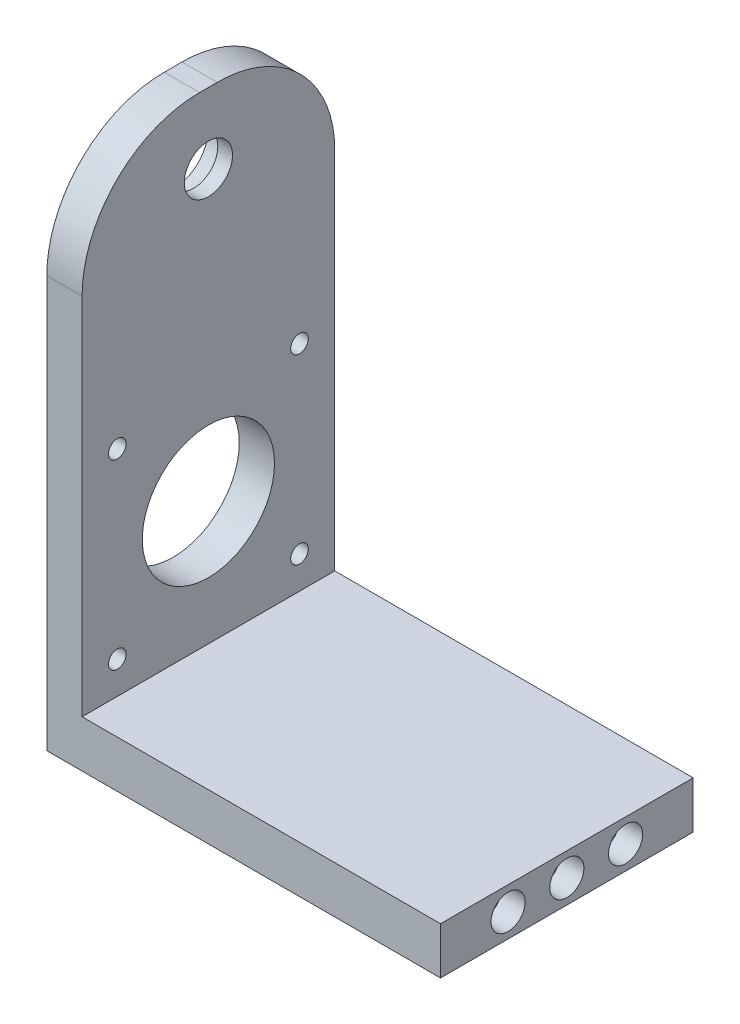
SolidWorks part; units mm, degrees
ref_plane "Front Plane" through (0, 0, 0) normal (0, 0, 1) x (1, 0, 0)
ref_plane "Top Plane" through (0, 0, 0) normal (0, 1, 0) x (1, 0, 0)
ref_plane "Right Plane" through (0, 0, 0) normal (1, 0, 0) x (0, 0, -1)
sketch "Sketch1" plane through (0, 0, 0) normal (0, 1, 0) x (1, 0, 0)
  line L1 (33.5, -21.5) -> (-33.5, -21.5)
  line L2 (33.5, -21.5) -> (33.5, 21.5)
  line L3 (33.5, 21.5) -> (-33.5, 21.5)
  line L4 (-33.5, -21.5) -> (-33.5, 21.5)
  line L5 (33.5, -21.5) -> (-33.5, 21.5) construction
  line L6 (33.5, 21.5) -> (-33.5, -21.5) construction
  point P0 (0, 0)
  dimension "D1" = 43
  dimension "D2" = 67
extrude "Boss-Extrude1" add sketch "Sketch1" along normal blind 8
sketch "Sketch2" plane through (0, 8, 0) normal (0, 1, 0) x (1, 0, 0)
  line L0 (-33.5, 21.5) -> (-33.5, -21.5)
  line L1 (-33.5, 21.5) -> (-27.5, 21.5)
  line L2 (-33.5, -21.5) -> (-27.5, -21.5)
  line L3 (-27.5, 21.5) -> (-27.5, -21.5)
  dimension "D1" = 6
extrude "Boss-Extrude2" add sketch "Sketch2" along normal blind 82
sketch "Sketch3" plane through (-27.5, 0, 0) normal (1, 0, 0) x (0, 0, -1)
  line L0 (0, 0) -> (0, 29) construction
  line L1 (-21.5, 8) -> (21.5, 8) construction
  line L2 (21.5, 29) -> (-21.5, 29) construction
  line L3 (-21.5, 90) -> (-21.5, 8) construction
  circle A0 centre (0, 29) radius 11.25
  circle A1 centre (-15.5, 44.5) radius 1.5
  circle A2 centre (15.5, 44.5) radius 1.5
  circle A3 centre (15.5, 13.5) radius 1.5
  circle A4 centre (-15.5, 13.5) radius 1.5
  point P11 (0, 29)
  dimension "D2" = 22.5
  dimension "D3" = 3
  dimension "D1" = 21
  dimension "D4" = 31
  dimension "D5" = 31
  dimension "D6" = 4
extrude "Cut-Extrude1" cut sketch "Sketch3" against normal up to next
sketch "Sketch4" plane through (-27.5, 0, 0) normal (1, 0, 0) x (0, 0, -1)
  line L0 (0, 0) -> (0, 90) construction
  line L1 (-21.5, 90) -> (21.5, 90) construction
  circle A0 centre (0, 29) radius 11.25 construction
  circle A1 centre (0, 29) radius 11.25 construction
  circle A2 centre (0, 78) radius 4.1
  dimension "D1" = 8.2
  dimension "D2" = 49
extrude "Cut-Extrude2" cut sketch "Sketch4" against normal up to next
fillet "Fillet1" radius 20 2 edges at (-30.5, 90, 21.5) (-30.5, 90, -21.5)
sketch "Sketch6" plane through (33.5, 0, 0) normal (1, 0, 0) x (0, 0, -1)
  line L0 (-21.5, 4) -> (21.5, 4) construction
  line L1 (-21.5, 8) -> (-21.5, 0) construction
  line L2 (21.5, 8) -> (21.5, 0) construction
  circle A0 centre (0, 4) radius 2.9
  circle A1 centre (10, 4) radius 2.9
  circle A2 centre (-10, 4) radius 2.9
  dimension "D1" = 5.8
  dimension "D2" = 21.5
  dimension "D3" = 2
  dimension "D4" = 2
extrude "Cut-Extrude4" cut sketch "Sketch6" against normal blind 4
sketch "Sketch7" plane through (-33.5, 0, 0) normal (-1, 0, 0) x (0, 0, 1)
  circle A0 centre (0, 78) radius 6
  dimension "D1" = 12
extrude "Cut-Extrude5" cut sketch "Sketch7" against normal blind 3.5
sketch "Sketch8" plane through (0, 8, 0) normal (0, 1, 0) x (1, 0, 0)
  line L0 (3, 21.5) -> (3, -21.5) construction
  line L1 (33.5, 21.5) -> (-27.5, 21.5) construction
  line L2 (-27.5, -21.5) -> (33.5, -21.5) construction
  line L3 (-27.5, 0) -> (33.5, 0) construction
  line L4 (-27.5, -21.5) -> (-27.5, 21.5) construction
  line L5 (33.5, -21.5) -> (33.5, 21.5) construction
  circle A0 centre (3, 0) radius 16
  dimension "D1" = 32
extrude "Cut-Extrude6" cut sketch "Sketch8" along normal blind 3.5 from surface at -8 starting at face at (0, 0, 0)
sketch "Sketch9" plane through (0, 3.5, 0) normal (0, -1, 0) x (1, 0, 0)
  line L0 (3, -12) -> (3, 12) construction
  circle A0 centre (3, 12) radius 2.9
  circle A1 centre (3, 0) radius 16
  circle A2 centre (3, 0) radius 16 construction
  circle A3 centre (15, 0) radius 2.9
  circle A4 centre (3, -12) radius 2.9
  circle A5 centre (-9, 0) radius 2.9
  point P6 (3, 0)
  dimension "D3" = 5.8
  dimension "D2" = 24
  dimension "D1" = 0
  dimension "D4" = 4
extrude "Cut-Extrude7" cut sketch "Sketch9" against normal blind 4
